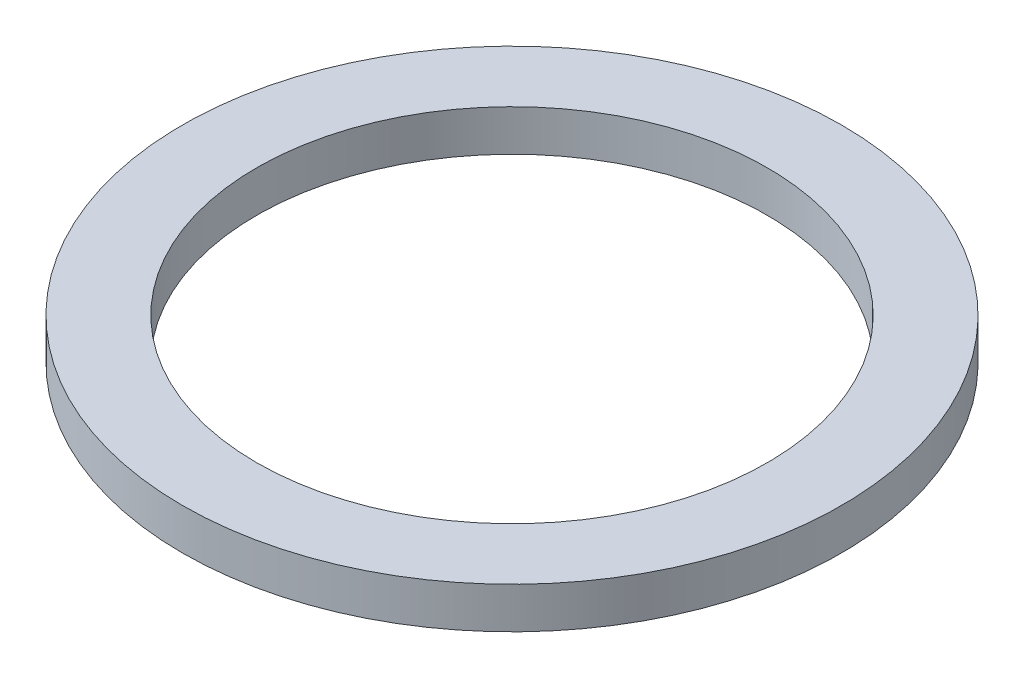
SolidWorks part; units mm, degrees
material "E-Glass Fiber"
ref_plane "Front Plane" through (0, 0, 0) normal (0, 0, 1) x (1, 0, 0)
ref_plane "Top Plane" through (0, 0, 0) normal (0, 1, 0) x (1, 0, 0)
ref_plane "Right Plane" through (0, 0, 0) normal (1, 0, 0) x (0, 0, -1)
sketch "Sketch1" plane through (0, 0, 0) normal (0, 1, 0) x (1, 0, 0)
  circle A0 centre (0, 0) radius 50.8
  circle A1 centre (0, 0) radius 39.37
  dimension "D1" = 101.6
  dimension "D2" = 78.74
extrude "Boss-Extrude1" add sketch "Sketch1" along normal blind 6.35
